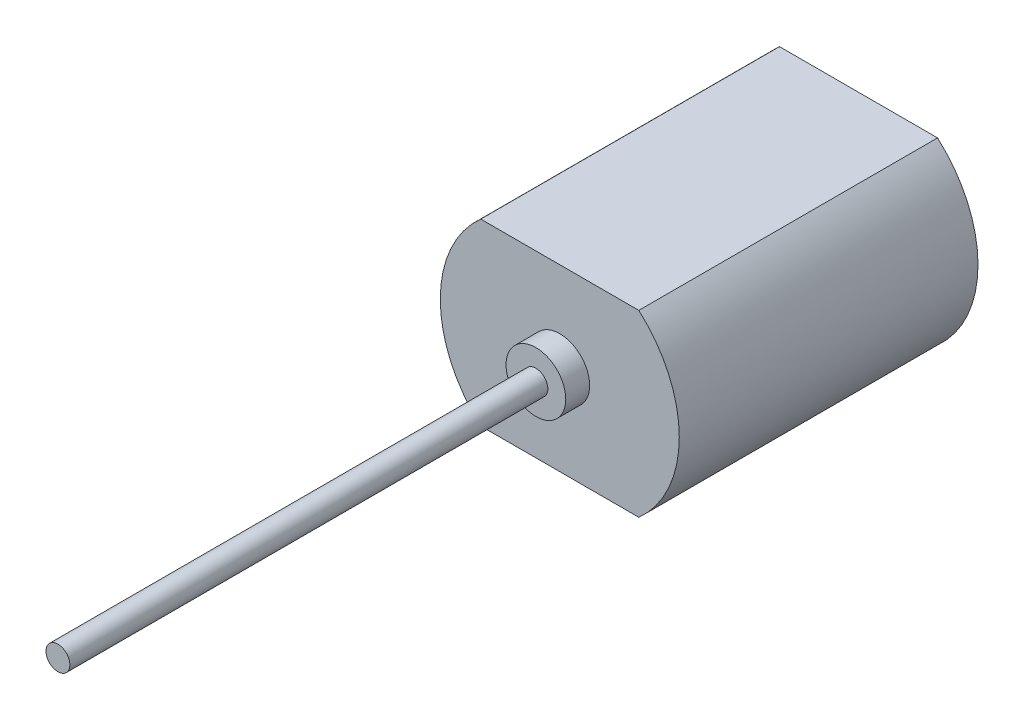
SolidWorks part; units mm, degrees
ref_plane "Plan de face" through (0, 0, 0) normal (0, 0, 1) x (1, 0, 0)
ref_plane "Plan de dessus" through (0, 0, 0) normal (0, 1, 0) x (1, 0, 0)
ref_plane "Plan de droite" through (0, 0, 0) normal (1, 0, 0) x (0, 0, -1)
sketch "Esquisse1" plane through (0, 0, 0) normal (0, 0, 1) x (1, 0, 0)
  line L0 (-6.6144, 7.5) -> (6.6144, 7.5)
  line L1 (-10, -7.5) -> (10, -7.5) construction
  line L2 (-10, -7.5) -> (-10, 7.5) construction
  line L3 (-10, 7.5) -> (10, 7.5) construction
  line L4 (10, -7.5) -> (10, 7.5) construction
  line L5 (-10, -7.5) -> (10, 7.5) construction
  line L6 (-10, 7.5) -> (10, -7.5) construction
  line L7 (6.6144, -7.5) -> (-6.6144, -7.5)
  arc A0 (-6.6144, 7.5) -> (-6.6144, -7.5) centre (0, 0) ccw
  arc A1 (6.6144, -7.5) -> (6.6144, 7.5) centre (0, 0) ccw
  point P0 (0, 0)
  dimension "D1" = 20
  dimension "D2" = 15
extrude "Boss.-Extru.1" add sketch "Esquisse1" along normal mid plane 25
sketch "Esquisse2" plane through (0, 0, 12.5) normal (0, 0, 1) x (1, 0, 0)
  circle A0 centre (0, 0) radius 2.5
  dimension "D1" = 5
extrude "Boss.-Extru.2" add sketch "Esquisse2" along normal blind 2
sketch "Esquisse3" plane through (0, 0, 14.5) normal (0, 0, 1) x (1, 0, 0)
  circle A0 centre (0, 0) radius 1
  dimension "D1" = 2
extrude "Boss.-Extru.3" add sketch "Esquisse3" along normal blind 40
